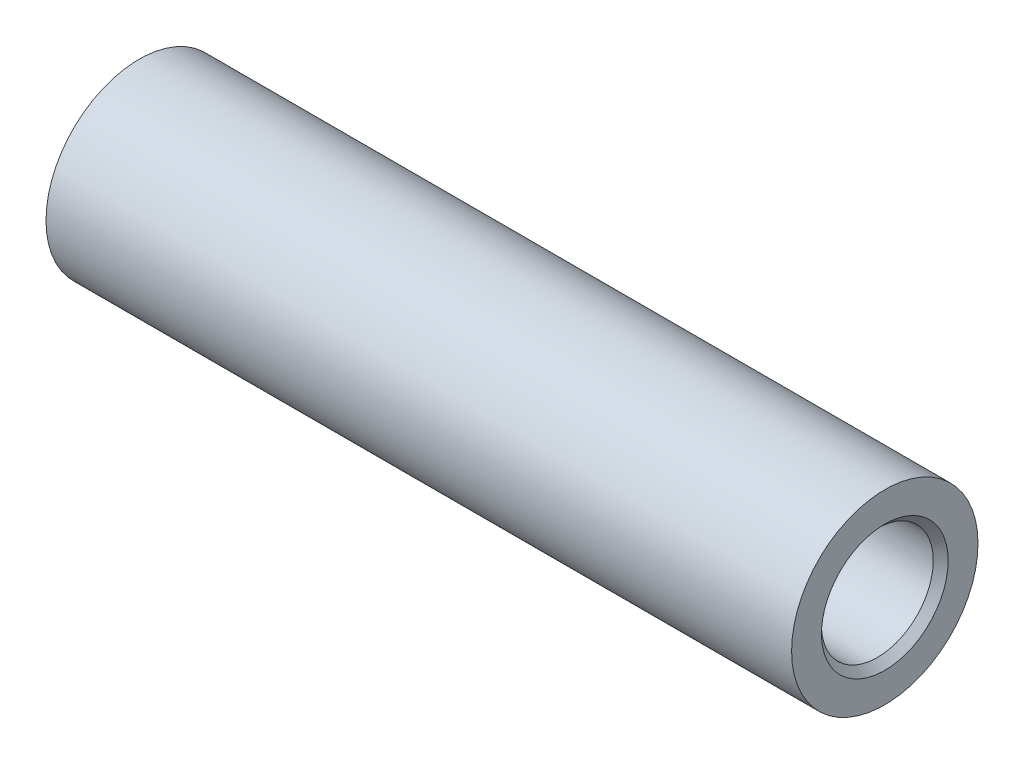
SolidWorks part; units mm, degrees
ref_plane "前视基准面" through (0, 0, 0) normal (0, 0, 1) x (1, 0, 0)
ref_plane "上视基准面" through (0, 0, 0) normal (0, 1, 0) x (1, 0, 0)
ref_plane "右视基准面" through (0, 0, 0) normal (1, 0, 0) x (0, 0, -1)
other "Configuration Table"
sketch "草图1" plane through (0, 0, 0) normal (1, 0, 0) x (0, 0, -1)
  circle A0 centre (0, 0) radius 5
  dimension "D1" = 10
extrude "凸台-拉伸1" add sketch "草图1" along normal blind 19 and the other way blind 21
sketch "草图3" plane through (19, 0, 0) normal (1, 0, 0) x (0, 0, -1)
  circle A0 centre (0, 0) radius 3
  dimension "D1" = 6
extrude "切除-拉伸1" cut sketch "草图3" against normal blind 17
sketch "草图4" plane through (-21, 0, 0) normal (-1, 0, 0) x (0, 0, 1)
  circle A0 centre (0, 0) radius 4
  dimension "D1" = 8
extrude "切除-拉伸2" cut sketch "草图4" against normal blind 21
sketch "草图5" plane through (2, 0, 0) normal (1, 0, 0) x (0, 0, -1)
  line L0 (-1.6583, 2.5) -> (1.6583, 2.5)
  circle A0 centre (0, 0) radius 3 construction
  arc A1 (1.6583, 2.5) -> (-1.6583, 2.5) centre (0, 0) ccw
  arc A2 (-1.6583, 2.5) -> (1.6583, 2.5) centre (0, 0) ccw construction
  dimension "D1" = 2.5
extrude "凸台-拉伸2" add sketch "草图5" along normal blind 12 separate body
sketch "草图6" plane through (0, 0, 0) normal (-1, 0, 0) x (0, 0, 1)
  line L0 (-1.8995, 3.5202) -> (1.9732, 3.4794)
  circle A0 centre (0, 0) radius 4 construction
  arc A1 (1.9732, 3.4794) -> (-1.8995, 3.5202) centre (0, 0) ccw
  arc A2 (-1.8995, 3.5202) -> (1.9732, 3.4794) centre (0, 0) ccw construction
  dimension "D1" = 3.5
extrude "凸台-拉伸3" add sketch "草图6" along normal blind 15
chamfer "倒角1" distance 0.4 angle 45 2 edges at (19, 0, -3) (-21, 0, 4)
fillet "圆角1" radius 0.4 1 edges at (14, 2.5, 0)
fillet "圆角2" radius 0.4 1 edges at (-15, 3.4998, 0.0368)
